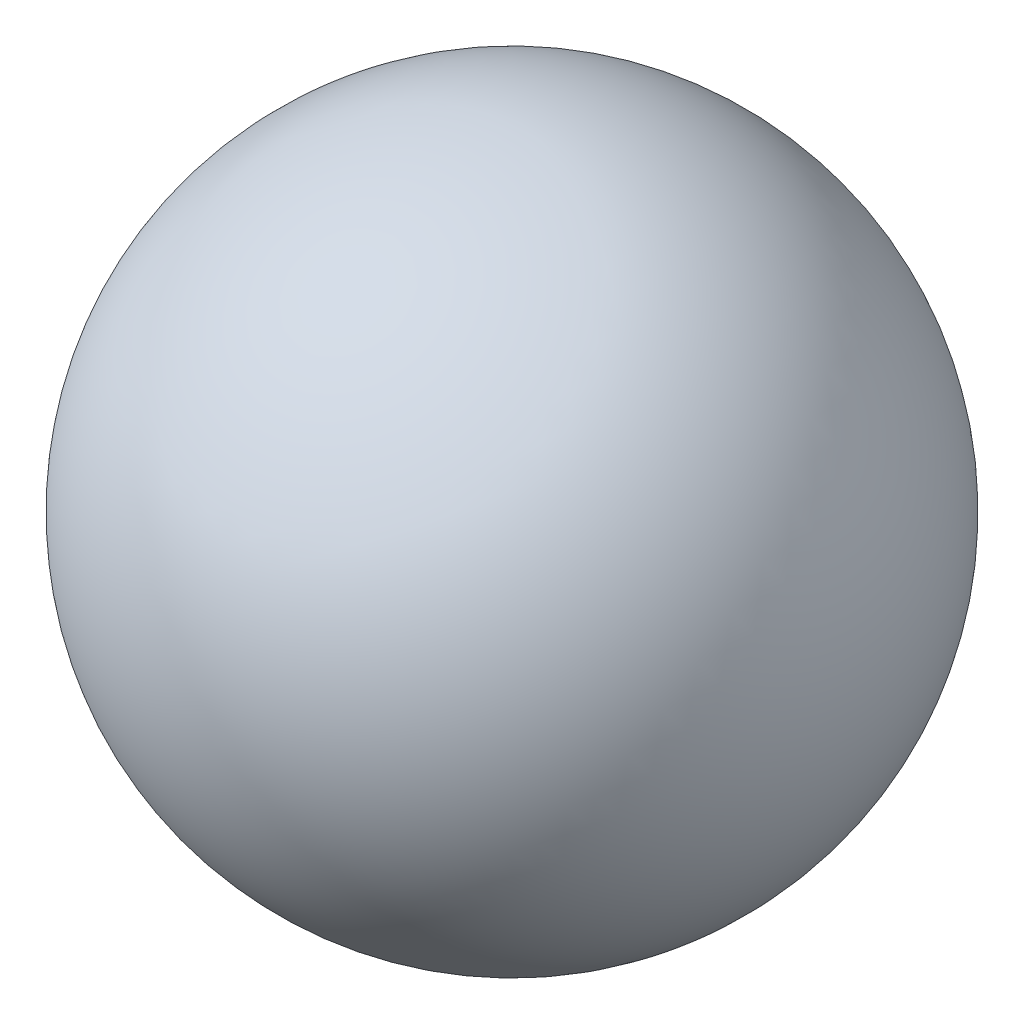
SolidWorks part; units mm, degrees
ref_plane "Front Plane" through (0, 0, 0) normal (0, 0, 1) x (1, 0, 0)
ref_plane "Top Plane" through (0, 0, 0) normal (0, 1, 0) x (1, 0, 0)
ref_plane "Right Plane" through (0, 0, 0) normal (1, 0, 0) x (0, 0, -1)
ref_plane "Plane1" through (0, 0, 0) normal (0, 0, -1) x (-1, 0, 0)
sketch "Sketch1" plane through (0, 0, 0) normal (0, 0, -1) x (-1, 0, 0)
  line L0 (1.605, 2.7799) -> (2.3638, 4.0941)
  line L1 (1.7947, 3.1085) -> (2.1232, 3.6776) construction
  arc A0 (2.3638, 4.0941) -> (1.605, 2.7799) centre (1.9844, 3.437) ccw
revolve "Revolve1" add sketch "Sketch1" angle 360 about L1
